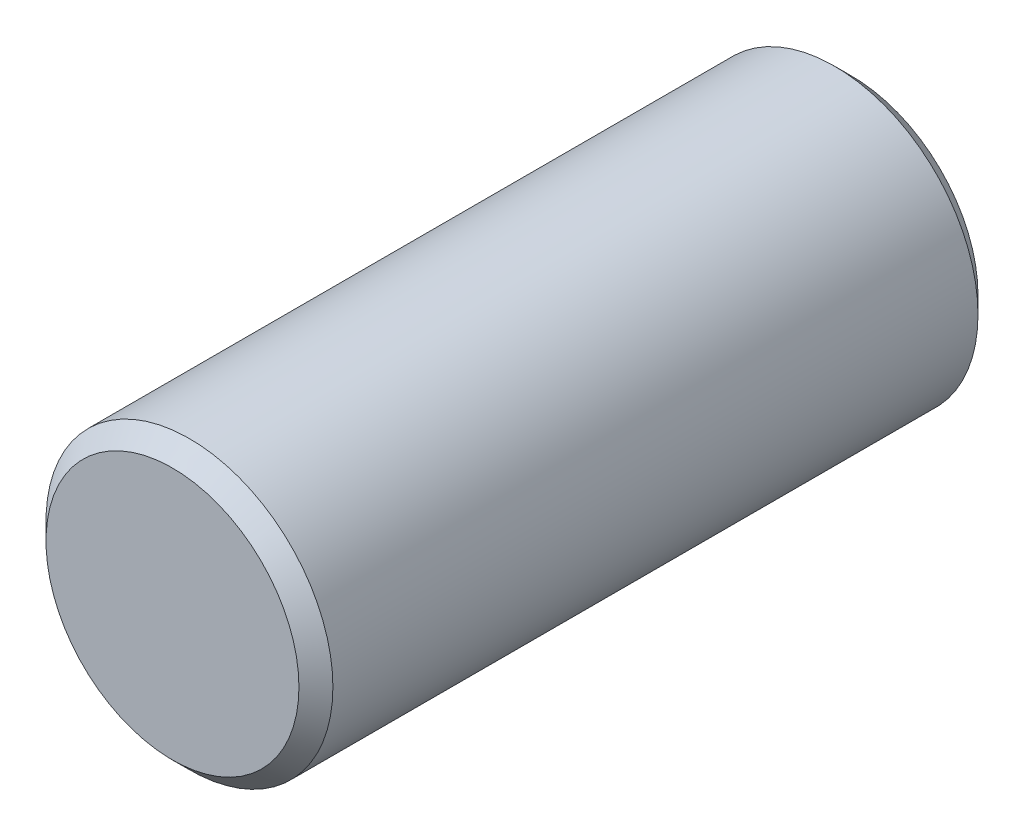
SolidWorks part; units mm, degrees
ref_plane "Front Plane" through (0, 0, 0) normal (0, 0, 1) x (1, 0, 0)
ref_plane "Top Plane" through (0, 0, 0) normal (0, 1, 0) x (1, 0, 0)
ref_plane "Right Plane" through (0, 0, 0) normal (1, 0, 0) x (0, 0, -1)
sketch "Sketch1" plane through (0, 0, 0) normal (0, 0, 1) x (1, 0, 0)
  circle A0 centre (0, 0) radius 16.9
  dimension "D1" = 33.8
extrude "Boss-Extrude1" add sketch "Sketch1" along normal blind 80
chamfer "Chamfer1" distance 2 angle 45 2 edges at (16.9, 0, 0) (16.9, 0, 80)
ref_plane "Plane1" through (0, 0, 40) normal (0, 0, -1) x (-1, 0, 0)
